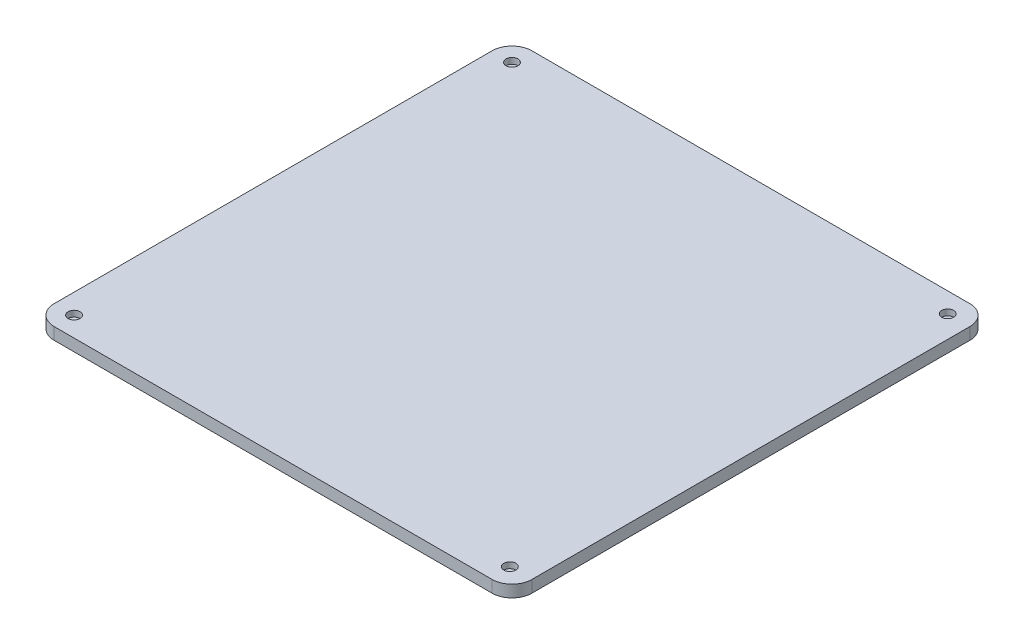
SolidWorks part; units mm, degrees
material "Vidrio"
ref_plane "Alzado" through (0, 0, 0) normal (0, 0, 1) x (1, 0, 0)
ref_plane "Planta" through (0, 0, 0) normal (0, 1, 0) x (1, 0, 0)
ref_plane "Vista lateral" through (0, 0, 0) normal (1, 0, 0) x (0, 0, -1)
sketch "Sketch1" plane through (0, 0, 0) normal (0, 1, 0) x (1, 0, 0)
  line L1 (-60, -60) -> (60, -60)
  line L2 (-60, -60) -> (-60, 60)
  line L3 (-60, 60) -> (60, 60)
  line L4 (60, -60) -> (60, 60)
  line L5 (-60, -60) -> (60, 60) construction
  line L6 (-60, 60) -> (60, -60) construction
  point P0 (0, 0)
  dimension "D1" = 120
  dimension "D2" = 120
extrude "Boss-Extrude1" add sketch "Sketch1" along normal blind 3
fillet "Fillet1" radius 5 4 edges at (-60, 1.5, -60) (60, 1.5, -60) (60, 1.5, 60) (-60, 1.5, 60)
sketch "Sketch2" plane through (0, 3, 0) normal (0, 1, 0) x (1, 0, 0)
  line L0 (-55, -60) -> (55, -60) construction
  circle A0 centre (-55, 55) radius 1.5
  arc A1 (-55, 60) -> (-60, 55) centre (-55, 55) ccw construction
  circle A2 centre (54.4511, 55) radius 1.5
  circle A3 centre (-55, -55) radius 1.5
  circle A4 centre (54.4511, -55) radius 1.5
  point P11 (-55, -53.6886)
  point P14 (0, 0)
  point P15 (0, 0)
  point P16 (0, 0)
  dimension "D1" = 3
  dimension "D2" = 5
extrude "Cut-Extrude1" cut sketch "Sketch2" against normal blind 1.5
